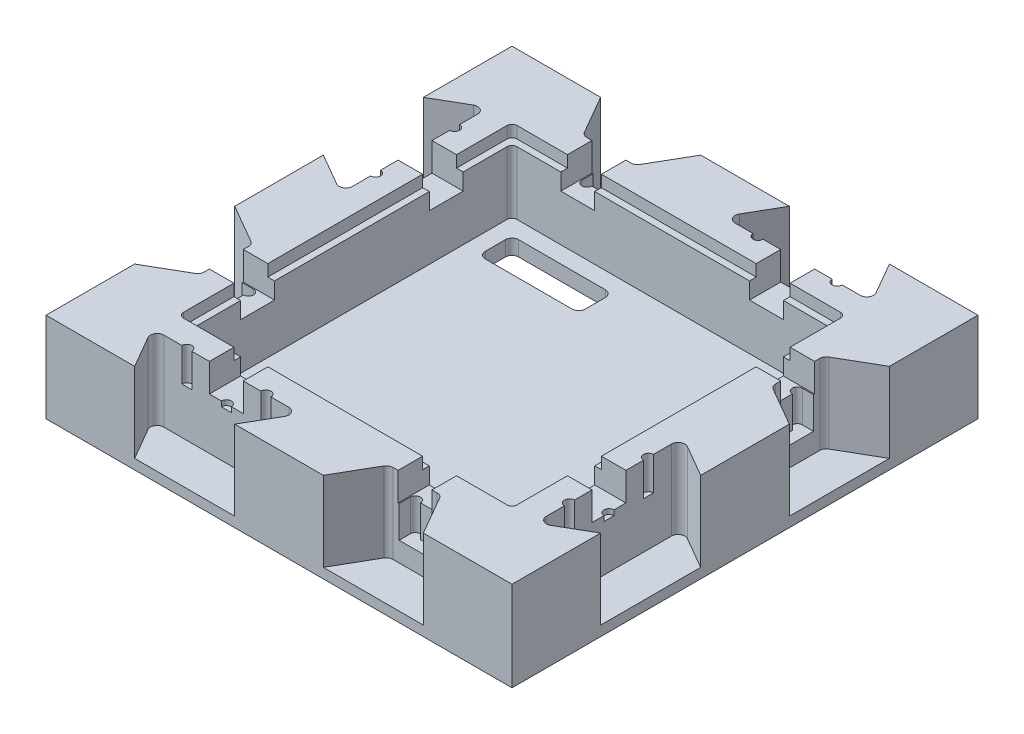
SolidWorks part; units mm, degrees
material "Macor"
ref_plane "Front Plane" through (0, 0, 0) normal (0, 0, 1) x (1, 0, 0)
ref_plane "Top Plane" through (0, 0, 0) normal (0, 1, 0) x (1, 0, 0)
ref_plane "Right Plane" through (0, 0, 0) normal (1, 0, 0) x (0, 0, -1)
sketch "Sketch1" plane through (0, 0, 0) normal (0, 1, 0) x (1, 0, 0)
  line L1 (-69.85, -69.85) -> (69.85, -69.85)
  line L2 (-69.85, -69.85) -> (-69.85, 69.85)
  line L3 (-69.85, 69.85) -> (69.85, 69.85)
  line L4 (69.85, -69.85) -> (69.85, 69.85)
  line L5 (-69.85, -69.85) -> (69.85, 69.85) construction
  line L6 (-69.85, 69.85) -> (69.85, -69.85) construction
  point P0 (0, 0)
  dimension "D1" = 139.7
extrude "Boss-Extrude1" add sketch "Sketch1" along normal mid plane 26.9
sketch "Sketch4" plane through (0, 13.45, 0) normal (0, 1, 0) x (1, 0, 0)
  line L0 (-43.2833, -69.85) -> (-50.5002, -57.35)
  line L1 (-69.85, -69.85) -> (69.85, -69.85) construction
  line L2 (-50.5002, -57.35) -> (-6.0665, -57.35)
  line L3 (-6.0665, -57.35) -> (-13.2833, -69.85)
  line L4 (-13.2833, -69.85) -> (-43.2833, -69.85)
  line L5 (43.2833, -69.85) -> (36.0665, -57.35)
  line L24 (43.2833, -69.85) -> (13.2833, -69.85)
  line L25 (-69.85, -69.85) -> (-43.2833, -69.85) construction
  line L26 (-13.2833, -69.85) -> (13.2833, -69.85) construction
  line L27 (43.2833, -69.85) -> (69.85, -69.85) construction
  line L28 (36.0665, -57.35) -> (20.5002, -57.35)
  line L30 (13.2833, -69.85) -> (20.5002, -57.35)
  dimension "D2" = 30
  dimension "D1" = 60
  dimension "D3" = 12.5
  dimension "D4" = 60
  dimension "D5" = 26.5667
extrude "Cut-Extrude2" cut sketch "Sketch4" against normal offset from surface 3 and the other way through all up to face at (0, -13.45, 0)
sketch "Sketch5" plane through (0, 13.45, 0) normal (0, 1, 0) x (1, 0, 0)
  line L0 (-50.5002, -57.35) -> (-6.0665, -57.35) construction
  line L1 (-6.0665, -57.35) -> (-50.5002, -57.35) construction
  line L2 (-50.5002, -57.35) -> (-41.6418, -57.35) construction
  line L3 (-41.6418, -57.35) -> (-38.6418, -57.35)
  line L4 (-38.6418, -57.35) -> (-29.7833, -57.35) construction
  line L5 (-29.7833, -57.35) -> (-26.7833, -57.35) construction
  line L6 (-26.7833, -57.35) -> (-17.9249, -57.35) construction
  line L7 (-17.9249, -57.35) -> (-14.9249, -57.35)
  line L8 (-14.9249, -57.35) -> (-6.0665, -57.35) construction
  line L9 (-29.7833, -57.35) -> (-26.7833, -57.35)
  arc A0 (-41.6418, -57.35) -> (-38.6418, -57.35) centre (-40.1418, -57.35) cw
  arc A1 (-29.7833, -57.35) -> (-26.7833, -57.35) centre (-28.2833, -57.35) cw
  arc A2 (-17.9249, -57.35) -> (-14.9249, -57.35) centre (-16.4249, -57.35) cw
  dimension "D1" = 1.5
extrude "Cut-Extrude3" cut sketch "Sketch5" against normal blind 10
sketch "Sketch6" plane through (0, 0, 57.35) normal (0, 0, 1) x (1, 0, 0)
  line L0 (20.5002, 13.45) -> (36.0665, 13.45) construction
  line L1 (23.2033, 13.45) -> (33.3633, 13.45)
  line L2 (23.2033, 13.45) -> (23.2033, 4.975)
  line L3 (23.2033, 4.975) -> (33.3633, 4.975)
  line L4 (33.3633, 13.45) -> (33.3633, 4.975)
  line L5 (20.5002, 13.45) -> (36.0665, 13.45) construction
  line L6 (-26.7833, 13.45) -> (-29.7833, 13.45) construction
  line L7 (-26.7833, 13.45) -> (-29.7833, 13.45) construction
  line L8 (-38.6418, 13.45) -> (-29.7833, 13.45) construction
  line L9 (-33.3633, 13.45) -> (-23.2033, 13.45)
  line L10 (-33.3633, 13.45) -> (-33.3633, 4.975)
  line L11 (-33.3633, 4.975) -> (-23.2033, 4.975)
  line L12 (-23.2033, 13.45) -> (-23.2033, 4.975)
  point P6 (28.2833, 13.45)
  point P7 (28.2833, 13.45)
  point P10 (-28.2833, 13.45)
  point P17 (-28.2833, 13.45)
  dimension "D1" = 10.16
  dimension "D2" = 8.475
extrude "Cut-Extrude4" cut sketch "Sketch6" against normal blind 20
sketch "Sketch7" plane through (0, 0, 57.35) normal (0, 0, 1) x (1, 0, 0)
  line L0 (23.2033, 4.975) -> (33.3633, 4.975) construction
  line L1 (23.2033, 4.975) -> (33.3633, 4.975) construction
  line L3 (23.5183, 4.975) -> (33.0483, 4.975)
  line L4 (23.5183, 4.975) -> (23.5183, -4.555)
  line L5 (23.5183, -4.555) -> (33.0483, -4.555)
  line L6 (33.0483, 4.975) -> (33.0483, -4.555)
  point P2 (28.2833, 4.975)
  point P7 (28.2833, 4.975)
  dimension "D1" = 9.53
extrude "Cut-Extrude5" cut sketch "Sketch7" against normal blind 3.375
sketch "Sketch8" plane through (0, 4.975, 0) normal (0, 1, 0) x (1, 0, 0)
  line L0 (33.0483, -53.975) -> (33.0483, -57.35) construction
  line L1 (23.5183, -53.975) -> (23.5183, -57.35) construction
  line L2 (33.0483, -53.975) -> (33.0483, -57.35) construction
  line L3 (23.5183, -53.975) -> (23.5183, -57.35) construction
  line L4 (33.0483, -53.975) -> (23.5183, -53.975) construction
  line L5 (23.5183, -53.975) -> (26.5183, -53.975)
  line L6 (30.0483, -53.975) -> (33.0483, -53.975)
  arc A0 (23.5183, -53.975) -> (26.5183, -53.975) centre (25.0183, -53.975) cw
  arc A1 (33.0483, -53.975) -> (30.0483, -53.975) centre (31.5483, -53.975) ccw
  dimension "D1" = 1.5
extrude "Cut-Extrude6" cut sketch "Sketch8" against normal up to surface (9.53 mm away) up to face at (28.2833, -4.555, 55.6625)
ref_axis "Axis1" through (0, 31.6464, 0) along (0, -1, 0)
fillet "Fillet1" radius 2 4 edges at (36.0665, 1.5, 57.35) (20.5002, 1.5, 57.35) (-50.5002, 1.5, 57.35) (-6.0665, 1.5, 57.35)
pattern_circular "CirPattern1" count 4 over 360 about axis through (0, 0, 0) along (0, 1, 0) of "Cut-Extrude2", "Cut-Extrude3", "Cut-Extrude4", "Cut-Extrude5", "Cut-Extrude6", "Fillet1"
sketch "Sketch9" plane through (0, 13.45, 0) normal (0, 1, 0) x (1, 0, 0)
  line L1 (-50, -50) -> (50, -50)
  line L2 (-50, -50) -> (-50, 50)
  line L3 (-50, 50) -> (50, 50)
  line L4 (50, -50) -> (50, 50)
  line L5 (-50, -50) -> (50, 50) construction
  line L6 (-50, 50) -> (50, -50) construction
  point P0 (0, 0)
  dimension "D1" = 100
extrude "Cut-Extrude7" cut sketch "Sketch9" against normal offset from surface (22.4 mm away) 4.5 up to face at (0, -13.45, 0)
sketch "Sketch10" plane through (0, -8.95, 0) normal (0, 1, 0) x (1, 0, 0)
  line L1 (-50, -50) -> (50, -50)
  line L2 (-50, -50) -> (-50, 50)
  line L3 (-50, 50) -> (50, 50)
  line L4 (50, -50) -> (50, 50)
  line L5 (-50, -50) -> (50, 50) construction
  line L6 (-50, 50) -> (50, -50) construction
  line L7 (-48, -48) -> (48, -48)
  line L8 (-48, -48) -> (-48, 48)
  line L9 (-48, 48) -> (48, 48)
  line L10 (48, -48) -> (48, 48)
  line L11 (-48, -48) -> (48, 48) construction
  line L12 (-48, 48) -> (48, -48) construction
  point P0 (0, 0)
  point P7 (0, 0)
  dimension "D1" = 96
extrude "Boss-Extrude2" add sketch "Sketch10" along normal offset from surface (18.9 mm away) 3.5 up to face at (-50.6535, 13.45, -49.963)
sketch "Sketch12" plane through (0, 0, 50) normal (0, 0, 1) x (1, 0, 0)
  line L1 (23.2033, 9.95) -> (33.3633, 9.95)
  line L2 (23.2033, 9.95) -> (23.2033, 4.975)
  line L3 (23.2033, 4.975) -> (33.3633, 4.975)
  line L4 (33.3633, 9.95) -> (33.3633, 4.975)
  line L5 (-33.3633, 9.95) -> (-23.2033, 9.95)
  line L6 (-33.3633, 9.95) -> (-33.3633, 4.975)
  line L7 (-33.3633, 4.975) -> (-23.2033, 4.975)
  line L8 (-23.2033, 9.95) -> (-23.2033, 4.975)
extrude "Cut-Extrude9" cut sketch "Sketch12" against normal blind 10
pattern_circular "CirPattern4" count 4 over 360 about axis through (0, 31.6464, 0) along (0, -1, 0) of "Cut-Extrude9"
sketch "Sketch11" plane through (0, -8.95, 0) normal (0, 1, 0) x (1, 0, 0)
  line L0 (-48, -48) -> (-48, -33.3633) construction
  line L1 (-43, 43) -> (-13, 43)
  line L2 (-43, 43) -> (-43, 33)
  line L3 (-43, 33) -> (-13, 33)
  line L4 (-13, 43) -> (-13, 33)
  line L5 (-48, 48) -> (-33.3633, 48) construction
  dimension "D1" = 5
  dimension "D2" = 5
  dimension "D3" = 10
  dimension "D4" = 30
extrude "Cut-Extrude8" cut sketch "Sketch11" against normal through all both and the other way through all
fillet "Fillet2" radius 2 4 edges at (-13, -11.2, -43) (-13, -11.2, -33) (-43, -11.2, -33) (-43, -11.2, -43)
pattern_circular "CirPattern3" count 2 over 360 about axis through (0, 0, 0) along (0, 1, 0) of "Fillet2", "Cut-Extrude8"
fillet "Fillet3" radius 1.5 8 edges at (48, 0.5, -48) (-48, 0.5, 48) (48, 0.5, 48) (-48, 0.5, -48) (-50, 11.7, 50) (50, 11.7, 50) (50, 11.7, -50) (-50, 11.7, -50)
equation "\"panel_width\"= 5.5in"
equation "\"finger_joint_width\"= 30mm"
equation "\"D1@Sketch1\"=\"panel_width\""
equation "\"D2@Sketch4\"=\"finger_joint_width\""
